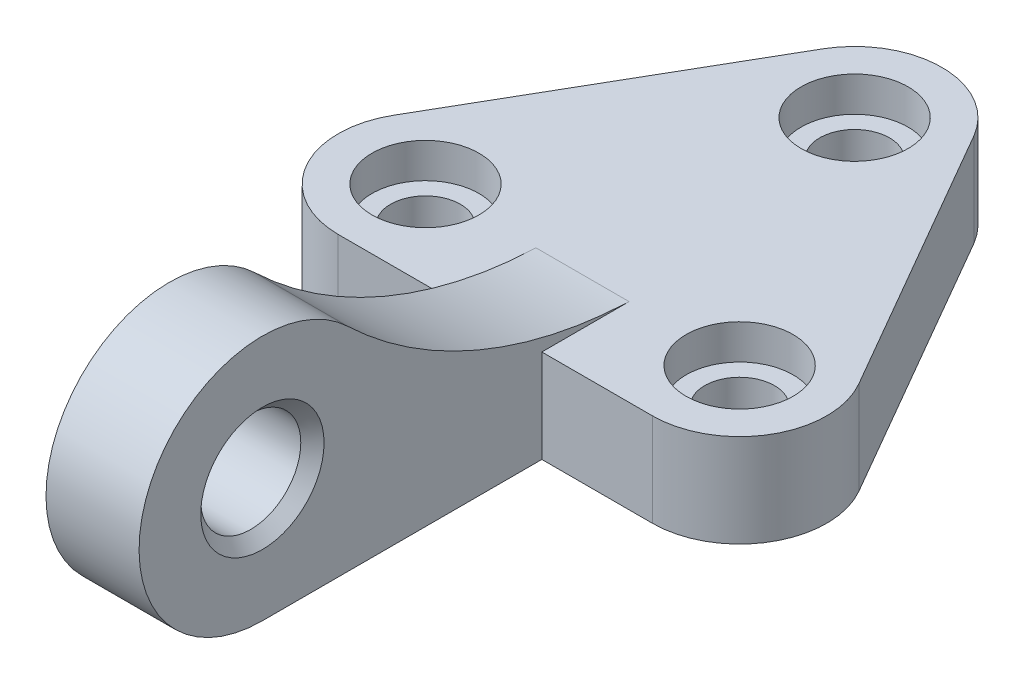
SolidWorks part; units mm, degrees
ref_plane "정면" through (0, 0, 0) normal (0, 0, 1) x (1, 0, 0)
ref_plane "윗면" through (0, 0, 0) normal (0, 1, 0) x (1, 0, 0)
ref_plane "우측면" through (0, 0, 0) normal (1, 0, 0) x (0, 0, -1)
sketch "Sketch1" plane through (0, 0, 0) normal (0, 1, 0) x (1, 0, 0)
  line L0 (64.9519, 0) -> (199.9519, 0)
  line L1 (232.4279, 56.25) -> (164.9279, 173.1634)
  line L2 (99.976, 173.1634) -> (32.476, 56.25)
  arc A0 (164.9279, 173.1634) -> (99.976, 173.1634) centre (132.4519, 154.4134) ccw
  arc A1 (64.9519, 0) -> (32.476, 56.25) centre (64.9519, 37.5) cw
  arc A2 (199.9519, 0) -> (232.4279, 56.25) centre (199.9519, 37.5) ccw
  point P8 (0, 0)
  dimension "D3" = 37.5
  dimension "D1" = 60
  dimension "D2" = 60
  dimension "D4" = 135
extrude "Boss-Extrude1" add sketch "Sketch1" along normal blind 40 contours L2 A1 L0 A2 L1 A0
sketch "Sketch4" plane through (0, 40, 0) normal (0, 1, 0) x (1, 0, 0)
  circle A0 centre (64.9519, 37.5) radius 23
  circle A1 centre (199.9519, 37.5) radius 23
  circle A2 centre (132.4519, 154.4134) radius 23
  dimension "D1" = 46
  dimension "D2" = 46
  dimension "D3" = 46
extrude "Cut-Extrude1" cut sketch "Sketch4" against normal blind 15
sketch "Sketch13" plane through (0, 40, 0) normal (0, 1, 0) x (1, 0, 0)
  line L0 (64.9519, 37.5) -> (199.9519, 37.5)
  line L1 (64.9519, 0) -> (199.9519, 0) construction
ref_plane "Plane2" through (132.4519, 0, 0) normal (1, 0, 0) x (0, 0, -1)
sketch "Sketch16" plane through (132.4519, 0, 0) normal (1, 0, 0) x (0, 0, -1)
  line L0 (-120.0866, 0) -> (0, 0)
  line L1 (0, 0) -> (37.5, 0)
  line L2 (0, 0) -> (56.25, 0) construction
  line L3 (37.5, 0) -> (37.5, 40)
  line L4 (56.25, 40) -> (0, 40) construction
  line L5 (191.9134, 0) -> (191.9134, 40) construction
  arc A0 (-83.3856, 91.2367) -> (-120.0866, 0) centre (-120.0866, 53) ccw
  arc A1 (37.5, 40) -> (-83.3856, 91.2367) centre (44.5531, 224.8655) cw
  point P1 (0, 0)
  point P13 (-102.0641, 103.5634)
  point P16 (0, 0)
  point P17 (-72.8703, 77.0754)
  point P18 (37.5, 225)
  point P19 (44.5531, 224.8655)
  dimension "D2" = 53
  dimension "D3" = 185
  dimension "D1" = 37.5
  dimension "D4" = 365
extrude "Boss-Extrude3" add sketch "Sketch16" along normal mid plane 40
hole_wizard "CSK for M2 Oval Head Machine Screw1" positions "3DSketch5" profile "Sketch17" countersink size "M2" standard "Ansi Metric" end condition up to next
sketch3d "3DSketch5"
  line L0 (152.4519, 53, 120.0866) -> (112.4519, 53, 120.0866) construction
  point P0 (152.4519, 53, 120.0866)
sketch "Sketch17" plane through (152.4519, 53, 120.0866) normal (0, 1, 0) x (0, 0, -1)
  line L0 (0, 0) -> (0, 40)
  line L1 (0, 40) -> (21.5, 40)
  line L2 (21.5, 40) -> (21.5, 5)
  line L3 (21.5, 5) -> (26.5, 0)
  line L5 (26.5, 0) -> (0, 0)
  line L6 (-21.5, 5) -> (-26.5, 0) construction
  line L11 (0, -6.35) -> (0, 107.95) construction
  dimension "관통 구멍 지름" = 43
  dimension "관통 구멍 깊이" = 40
  dimension "표면 카운터싱크 지름" = 53
  dimension "표면 카운터싱크 각도" = 90
hole_wizard "M2 Clearance Hole1" positions "3DSketch6" profile "Sketch18" hole size "M2" standard "Ansi Metric"
sketch3d "3DSketch6"
  line L0 (64.9519, 25, -37.5) -> (64.9519, 40, -37.5) construction
  line L1 (132.4519, 25, -154.4134) -> (132.4519, 40, -154.4134) construction
  point P0 (64.9519, 25, -37.5)
  point P4 (199.9519, 40, -37.5)
  point P7 (132.4519, 25, -154.4134)
sketch "Sketch18" plane through (64.9519, 25, -37.5) normal (1, 0, 0) x (0, 0, 1)
  line L0 (0, 0) -> (0, 25)
  line L1 (0, 25) -> (15, 25)
  line L2 (15, 25) -> (15, 0)
  line L5 (15, 0) -> (0, 0)
  line L11 (0, -6.35) -> (0, 107.95) construction
  dimension "관통 구멍 지름" = 30
  dimension "관통 구멍 깊이" = 25
